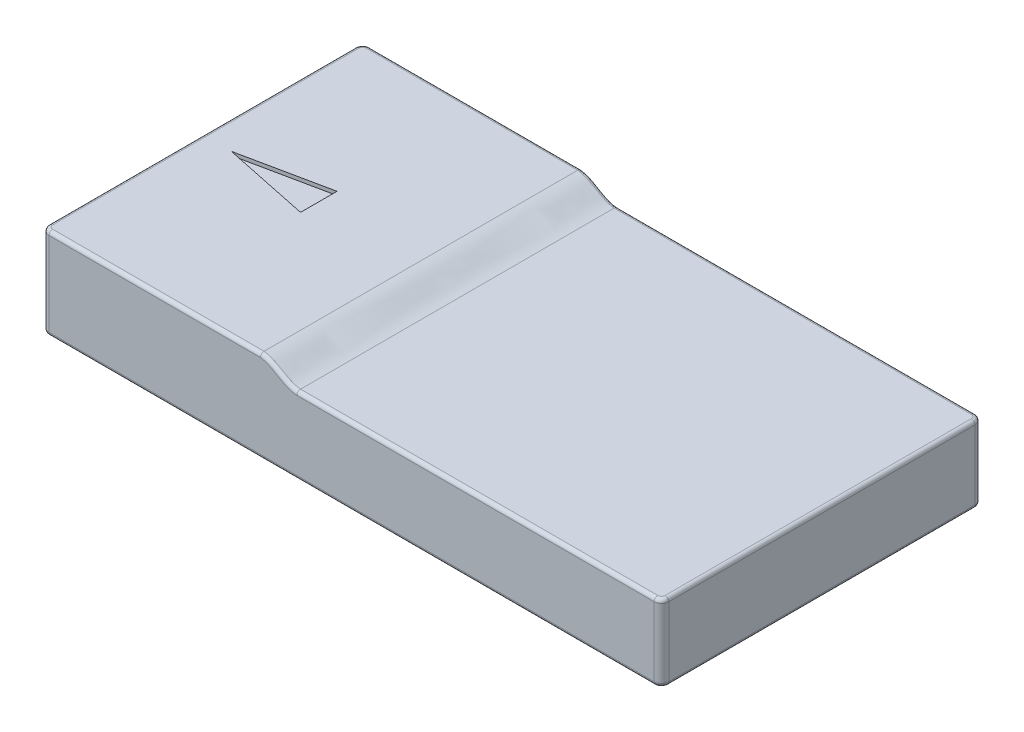
SolidWorks part; units mm, degrees
material "ABS"
ref_plane "Front Plane" through (0, 0, 0) normal (0, 0, 1) x (1, 0, 0)
ref_plane "Top Plane" through (0, 0, 0) normal (0, 1, 0) x (1, 0, 0)
ref_plane "Right Plane" through (0, 0, 0) normal (1, 0, 0) x (0, 0, -1)
sketch "Sketch1" plane through (0, 0, 0) normal (0, 1, 0) x (1, 0, 0)
  line L0 (-42.5, 22) -> (-42.5, -22)
  line L1 (-42.5, -22) -> (42.5, -22)
  line L2 (42.5, -22) -> (42.5, 22)
  line L3 (42.5, 22) -> (-42.5, 22)
  point P5 (0, -22)
  point P7 (42.5, 0)
  dimension "D1" = 44
  dimension "D2" = 85
sketch "Sketch2" plane through (0, 0, 0) normal (0, 0, 1) x (1, 0, 0)
  line L0 (42.5, 0) -> (-42.5, 0) construction
  line L1 (42.5, 0) -> (-42.5, 0) construction
  line L2 (-42.5, 12.5) -> (-12.5, 12.5)
  line L3 (42.5, 10.5) -> (-7.5, 10.5)
  line L4 (-42.5, 0) -> (-42.5, 12.5) construction
  line L5 (42.5, 0) -> (42.5, 10.5) construction
  line L6 (-42.5, 12.5) -> (-42.5, 22.5)
  line L7 (-42.5, 22.5) -> (42.5, 22.5)
  line L8 (42.5, 22.5) -> (42.5, 10.5)
  spline S0 degree 3 poles (-12.5, 12.5) (-10.6234, 12.323) (-9.3766, 10.677) (-7.5, 10.5) knots 0 0 0 0 1 1 1 1
  dimension "D1" = 12.5
  dimension "D2" = 10.5
  dimension "D3" = 30
  dimension "D4" = 50
  dimension "D5" = 1.6
  dimension "D6" = 1.6
  dimension "D7" = 0.5
  dimension "D8" = 0.5
  dimension "D9" = 10
extrude "Boss-Extrude1" add sketch "Sketch1" along normal blind 15
extrude "Cut-Extrude1" cut sketch "Sketch2" against normal through all both and the other way through all
sketch "Sketch3" plane through (0, 12.5, 0) normal (0, 1, 0) x (1, 0, 0)
  line L0 (-20, 22) -> (-20, -22) construction
  line L1 (-42.5, 22) -> (-12.5, 22) construction
  line L2 (-42.5, -22) -> (-12.5, -22) construction
  line L3 (-12.5, 22) -> (-12.5, -22) construction
  text T0 "pixhawk 6c      "
  point P6 (-20, 0)
  dimension "D1" = 20
  dimension "D2" = 12.5
  dimension "D3" = 22
fillet "Fillet1" radius 1 4 edges at (-42.5, 6.25, -22) (42.5, 5.25, -22) (42.5, 5.25, 22) (-42.5, 6.25, 22)
fillet "Fillet2" radius 0.5 12 edges at (-27, 12.5, -22) (-42.2071, 12.5, -21.7071) (-42.5, 12.5, 0) (-42.2071, 12.5, 21.7071) (17, 10.5, -22) (42.2071, 10.5, -21.7071) (42.5, 10.5, 0) (42.2071, 10.5, 21.7071) (-27, 12.5, 22) (17, 10.5, 22)
fillet "Fillet3" radius 0.5 8 edges at (-42.2071, 0, 21.7071) (-42.5, 0, 0) (-42.2071, 0, -21.7071) (0, 0, -22) (42.2071, 0, -21.7071) (42.5, 0, 0) (42.2071, 0, 21.7071) (0, 0, 22)
sketch "Sketch4" plane through (0, 12.5, 0) normal (0, 1, 0) x (1, 0, 0)
  line L0 (0, 0) -> (-42.5, 0) construction
  line L1 (-42.5, -21) -> (-42.5, 21) construction
  line L2 (-38.5, 0) -> (-26.5, 2.5)
  line L3 (-26.5, 2.5) -> (-26.5, -2.5)
  line L4 (-26.5, -2.5) -> (-38.5, 0)
  point P8 (-26.5, 0)
  dimension "D1" = 4
  dimension "D2" = 12
  dimension "D3" = 5
extrude "Cut-Extrude3" cut sketch "Sketch4" against normal blind 0.5
